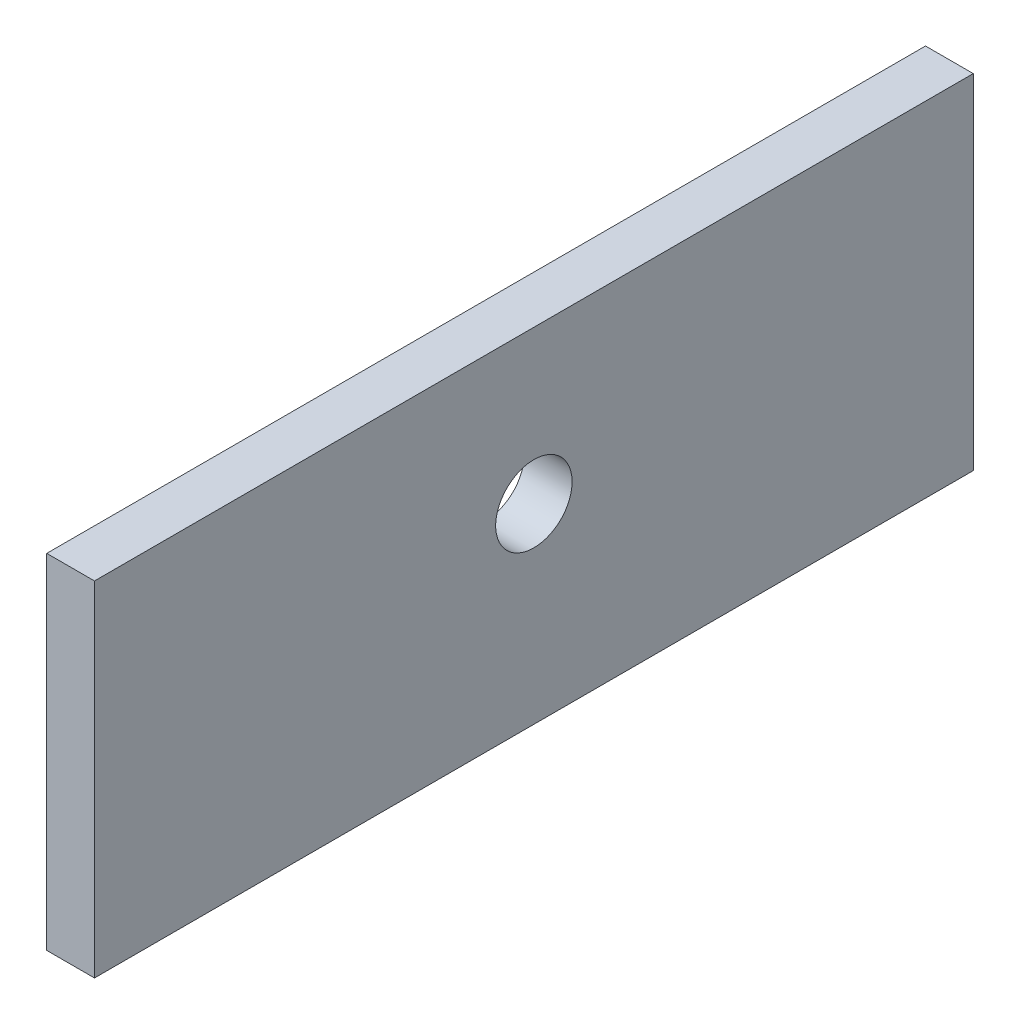
SolidWorks part; units mm, degrees
ref_plane "前视" through (0, 0, 0) normal (0, 0, 1) x (1, 0, 0)
ref_plane "上视" through (0, 0, 0) normal (0, 1, 0) x (1, 0, 0)
ref_plane "右视" through (0, 0, 0) normal (1, 0, 0) x (0, 0, -1)
sketch "草图1" plane through (0, 0, 0) normal (1, 0, 0) x (0, 0, -1)
  line L1 (0, 0) -> (46, 0)
  line L2 (0, 0) -> (0, 18)
  line L3 (0, 18) -> (46, 18)
  line L4 (46, 0) -> (46, 18)
  dimension "D1" = 46
  dimension "D2" = 18
extrude "凸台-拉伸1" add sketch "草图1" along normal blind 2.5
sketch "草图2" plane through (2.5, 0, 0) normal (1, 0, 0) x (0, 0, -1)
  line L0 (0, 0) -> (46, 0) construction
  circle A0 centre (23, 10) radius 2
  point P2 (23, 0)
  dimension "D1" = 4
  dimension "D2" = 10
extrude "切除-拉伸2" cut sketch "草图2" against normal through all
